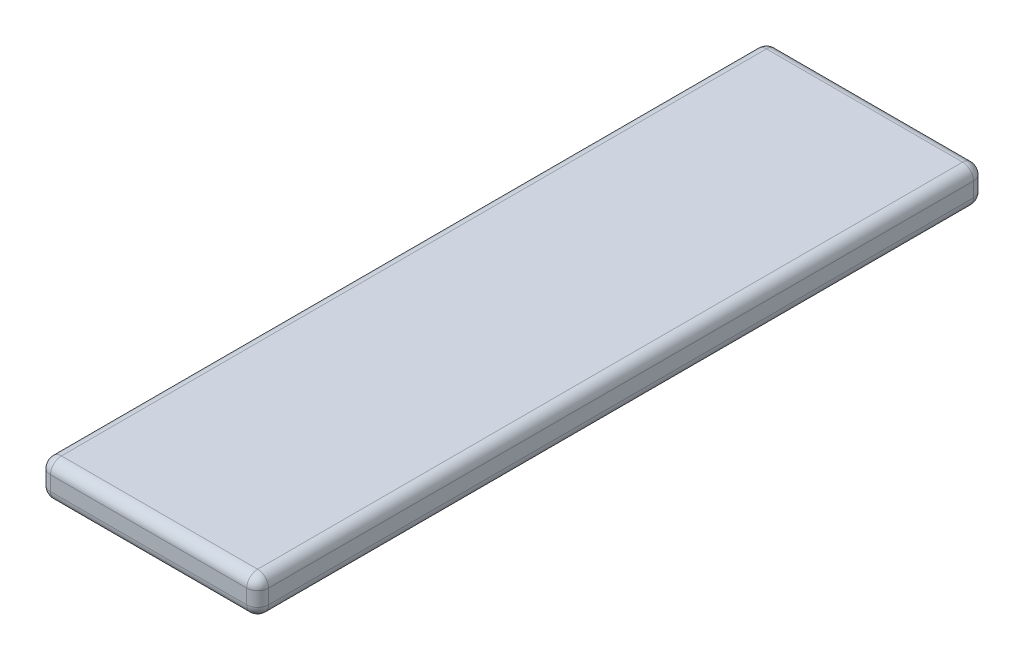
SolidWorks part; units mm, degrees
ref_plane "Front Plane" through (0, 0, 0) normal (0, 0, 1) x (1, 0, 0)
ref_plane "Top Plane" through (0, 0, 0) normal (0, 1, 0) x (1, 0, 0)
ref_plane "Right Plane" through (0, 0, 0) normal (1, 0, 0) x (0, 0, -1)
sketch "Sketch2" plane through (0, 0, 0) normal (0, 1, 0) x (1, 0, 0)
  line L1 (300, 1000) -> (-300, 1000)
  line L2 (300, 1000) -> (300, -1000)
  line L3 (300, -1000) -> (-300, -1000)
  line L4 (-300, 1000) -> (-300, -1000)
  line L5 (300, 1000) -> (-300, -1000) construction
  line L6 (300, -1000) -> (-300, 1000) construction
  point P0 (0, 0)
  dimension "D1" = 600
  dimension "D2" = 2000
extrude "Boss-Extrude1" add sketch "Sketch2" along normal blind 100
fillet "Fillet1" radius 30 12 edges at (0, 0, 1000) (-300, 50, 1000) (-300, 0, 0) (-300, 50, -1000) (0, 0, -1000) (300, 50, 1000) (300, 50, -1000) (300, 0, 0) (0, 100, -1000) (300, 100, 0) (0, 100, 1000) (-300, 100, 0)
